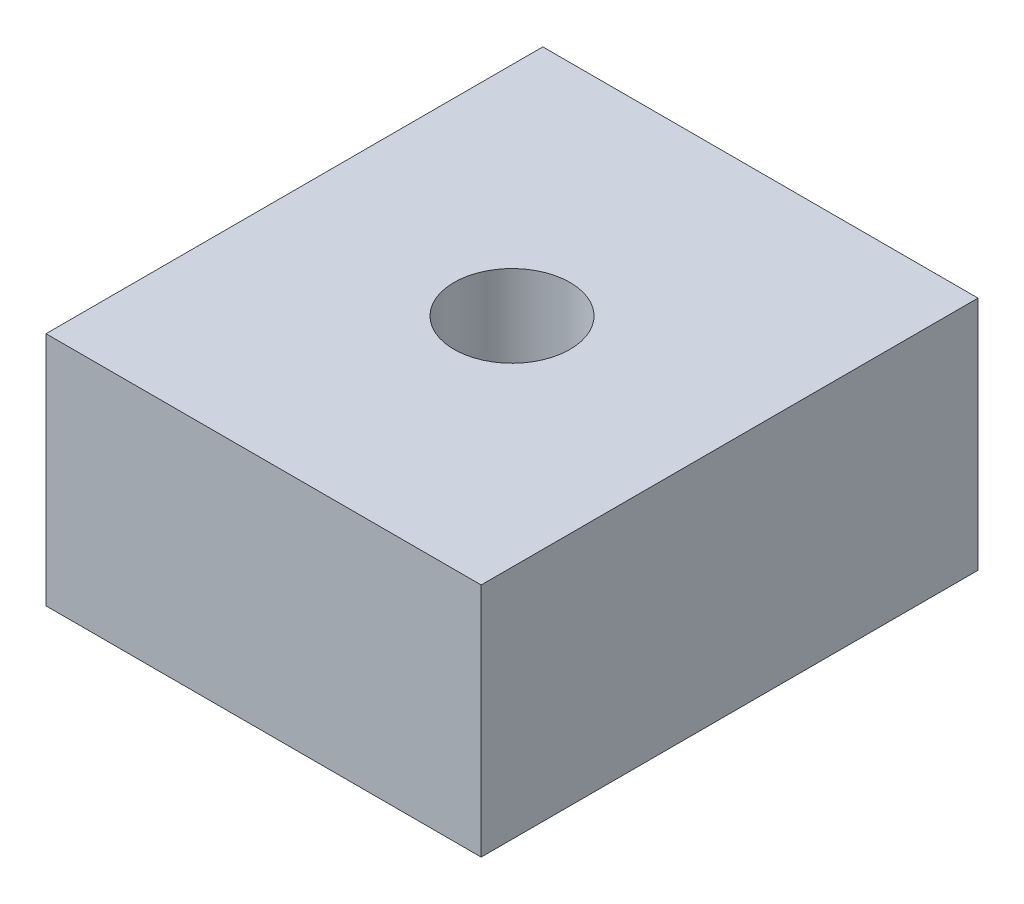
SolidWorks part; units mm, degrees
ref_plane "Ebene vorne" through (0, 0, 0) normal (0, 0, 1) x (1, 0, 0)
ref_plane "Ebene oben" through (0, 0, 0) normal (0, 1, 0) x (1, 0, 0)
ref_plane "Ebene rechts" through (0, 0, 0) normal (1, 0, 0) x (0, 0, -1)
sketch "Sketch4" plane through (0, 0, 0) normal (0, 1, 0) x (1, 0, 0)
  line L0 (0, 0) -> (0, 6.85) construction
  line L1 (-6, -6.85) -> (6, -6.85)
  line L2 (-6, -6.85) -> (-6, 6.85)
  line L3 (-6, 6.85) -> (6, 6.85)
  line L4 (6, -6.85) -> (6, 6.85)
  line L5 (0, 0) -> (-6, 0) construction
  dimension "D1" = 12
  dimension "D2" = 13.7
extrude "Boss-Extrude2" add sketch "Sketch4" along normal blind 6.5
sketch "Sketch3" plane through (0, 0, 0) normal (0, -1, 0) x (1, 0, 0)
  line L1 (1.6386, -2.9203) -> (3.3484, -0.0411)
  line L2 (3.3484, -0.0411) -> (1.7098, 2.8792)
  line L3 (1.7098, 2.8792) -> (-1.6386, 2.9203)
  line L4 (-1.6386, 2.9203) -> (-3.3484, 0.0411)
  line L5 (-3.3484, 0.0411) -> (-1.7098, -2.8792)
  line L6 (-1.7098, -2.8792) -> (1.6386, -2.9203)
  circle A0 centre (0, 0) radius 2.9 construction
  dimension "D1" = 5.8
extrude "Cut-Extrude1" cut sketch "Sketch3" against normal blind 3 contours L6 L1 L2 L3 L4 L5
sketch "Sketch5" plane through (0, 0, 0) normal (0, -1, 0) x (1, 0, 0)
  circle A0 centre (0, 0) radius 1.6
  dimension "D1" = 3.2
extrude "Cut-Extrude2" cut sketch "Sketch5" against normal through all both and the other way through all
